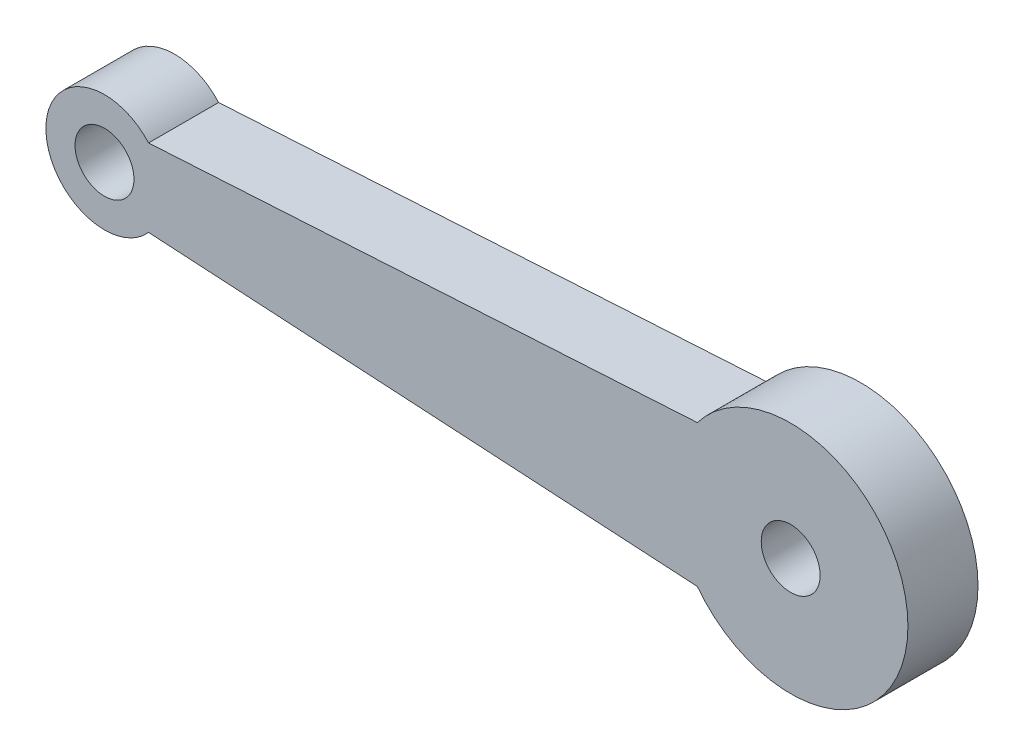
SolidWorks part; units mm, degrees
ref_plane "Front Plane" through (0, 0, 0) normal (0, 0, 1) x (1, 0, 0)
ref_plane "Top Plane" through (0, 0, 0) normal (0, 1, 0) x (1, 0, 0)
ref_plane "Right Plane" through (0, 0, 0) normal (1, 0, 0) x (0, 0, -1)
sketch "Sketch1" plane through (0, 0, 0) normal (0, 0, 1) x (1, 0, 0)
  line L0 (-54.6219, 0) -> (-49.5969, 0) construction
  line L1 (47.1961, -12.9806) -> (46.8312, 0) construction
  line L2 (46.4909, -12.1052) -> (-47.1138, -6.6052)
  line L3 (46.4909, 12.1052) -> (-47.1138, 6.6052)
  line L4 (42.4114, 0) -> (46.8312, 0) construction
  line L5 (57.3864, 0) -> (62.4114, 0) construction
  arc A0 (-47.1138, 6.6052) -> (-47.1138, -6.6052) centre (-54.6219, 0) ccw
  arc A1 (46.4909, -12.1052) -> (46.4909, 12.1052) centre (62.4114, 0) ccw
  circle A2 centre (-54.6219, 0) radius 5.025
  circle A3 centre (62.4114, 0) radius 5.025
  dimension "D2" = 20
  dimension "D3" = 40
  dimension "D4" = 10.05
  dimension "D5" = 10.05
  dimension "D1" = 117.0333
extrude "Boss-Extrude1" add sketch "Sketch1" along normal blind 11.95
